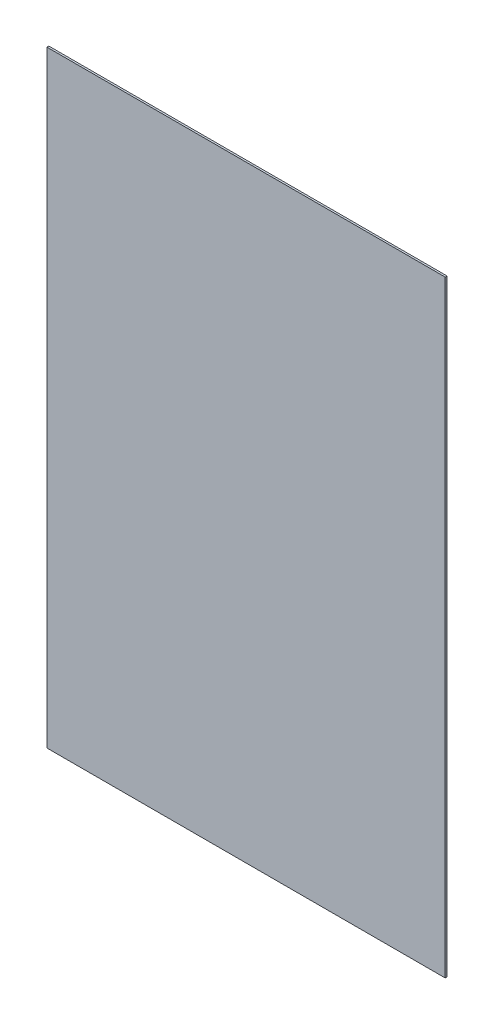
SolidWorks part; units mm, degrees
ref_plane "前视基准面" through (0, 0, 0) normal (0, 0, 1) x (1, 0, 0)
ref_plane "上视基准面" through (0, 0, 0) normal (0, 1, 0) x (1, 0, 0)
ref_plane "右视基准面" through (0, 0, 0) normal (1, 0, 0) x (0, 0, -1)
sketch "草图1" plane through (0, 0, 0) normal (0, 0, 1) x (1, 0, 0)
  line L1 (0, 0) -> (-210, 0)
  line L2 (0, 0) -> (0, 320)
  line L3 (0, 320) -> (-210, 320)
  line L4 (-210, 0) -> (-210, 320)
  dimension "D1" = 320
  dimension "D2" = 210
extrude "凸台-拉伸1" add sketch "草图1" along normal blind 1
